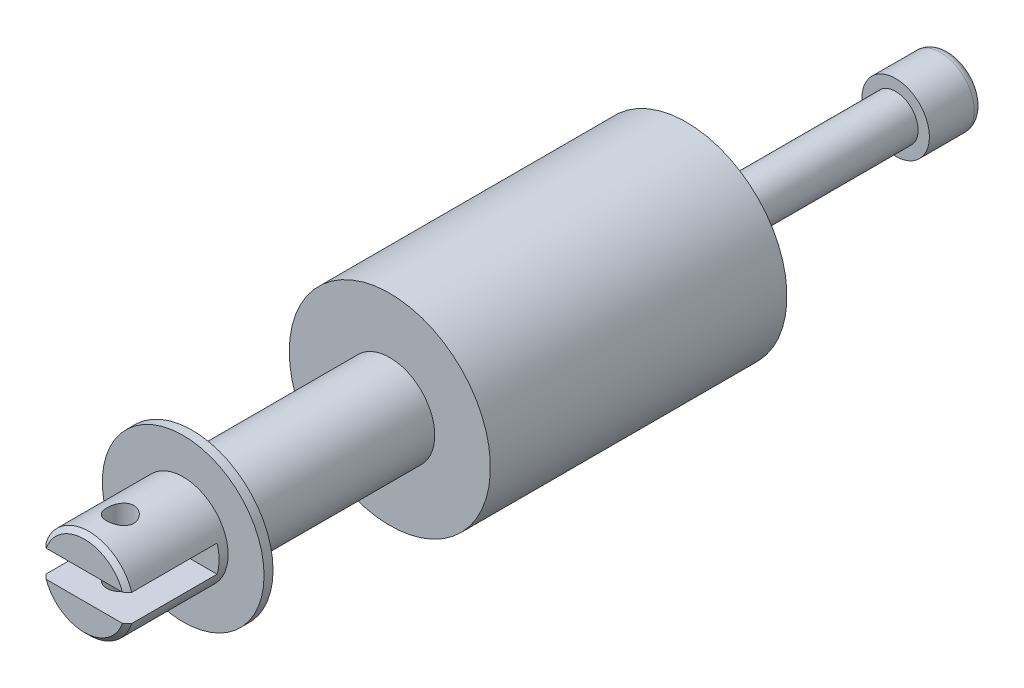
SolidWorks part; units mm, degrees
ref_plane "前视基准面" through (0, 0, 0) normal (0, 0, 1) x (1, 0, 0)
ref_plane "上视基准面" through (0, 0, 0) normal (0, 1, 0) x (1, 0, 0)
ref_plane "右视基准面" through (0, 0, 0) normal (1, 0, 0) x (0, 0, -1)
sketch "草图1" plane through (0, 0, 0) normal (0, 1, 0) x (1, 0, 0)
  line L0 (0, 46.1132) -> (0, -82.9941) construction
  line L2 (2.5, 14.9289) -> (2.5, -8.3711)
  line L3 (2.5, -8.3711) -> (11.1954, -8.3711)
  line L4 (11.1954, -8.3711) -> (11.1954, -41.3711)
  line L5 (11.1954, -41.3711) -> (5, -41.3711)
  line L6 (5, -41.3711) -> (5, -75.3711)
  line L13 (2.5, 20.9289) -> (0, 20.9289)
  line L14 (0, -75.3711) -> (5, -75.3711)
  line L15 (0, -75.3711) -> (0, 20.9289)
  line L16 (2.5, 14.9289) -> (3.75, 14.9289)
  line L17 (3.75, 14.9289) -> (3.75, 20.9289)
  line L18 (3.75, 20.9289) -> (2.5, 20.9289)
  point P12 (0, -75.3711)
  point P17 (0, 20.9289)
  dimension "D1" = 96.3
  dimension "D2" = 2.5
  dimension "D3" = 5
  dimension "D4" = 34
  dimension "D5" = 33
  dimension "D6" = 6
  dimension "D7" = 3.75
revolve "旋转1" add sketch "草图1" angle 360 about L0
chamfer "倒角1" distance 0.5 angle 45 1 edges at (-5, 0, 75.3711)
sketch "草图3" plane through (0, 0, 75.3711) normal (0, 0, 1) x (1, 0, 0)
  line L1 (-8, 1.5) -> (8, 1.5)
  line L2 (-8, 1.5) -> (-8, -1.5)
  line L3 (-8, -1.5) -> (8, -1.5)
  line L4 (8, 1.5) -> (8, -1.5)
  line L5 (-8, 1.5) -> (8, -1.5) construction
  line L6 (-8, -1.5) -> (8, 1.5) construction
  point P0 (0, 0)
  dimension "D1" = 3
  dimension "D2" = 16
extrude "切除-拉伸1" cut sketch "草图3" against normal blind 10
sketch "草图4" plane through (0, 0, 0) normal (0, 1, 0) x (1, 0, 0)
  line L0 (-4.2426, -75.3711) -> (4.2426, -75.3711) construction
  circle A0 centre (0, -71.3711) radius 1.5
  dimension "D1" = 3
  dimension "D2" = 4
extrude "切除-拉伸2" cut sketch "草图4" along normal mid plane 22
fillet "圆角1" radius 1 1 edges at (-3.75, 0, -20.9289)
ref_plane "基准面1" through (0, 0, 64.3711) normal (0, 0, 1) x (1, 0, 0)
sketch "草图5" plane through (0, 0, 64.3711) normal (0, 0, 1) x (1, 0, 0)
  circle A0 centre (0, 0) radius 9
extrude "凸台-拉伸1" add sketch "草图5" against normal blind 1
